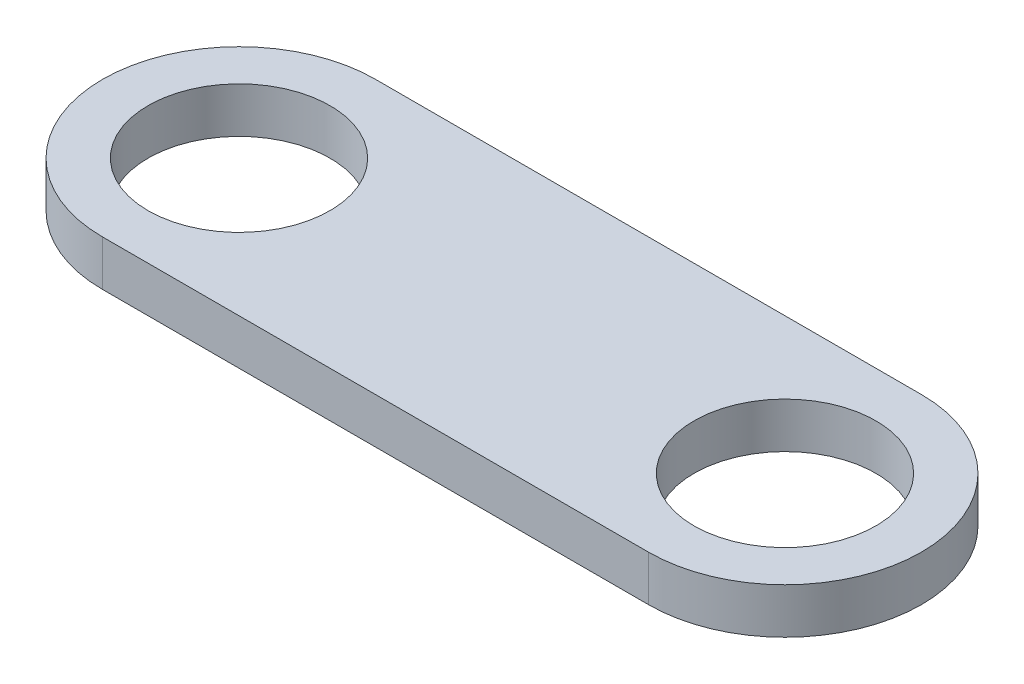
SolidWorks part; units mm, degrees
ref_plane "Front Plane" through (0, 0, 0) normal (0, 0, 1) x (1, 0, 0)
ref_plane "Top Plane" through (0, 0, 0) normal (0, 1, 0) x (1, 0, 0)
ref_plane "Right Plane" through (0, 0, 0) normal (1, 0, 0) x (0, 0, -1)
sketch "Sketch2" plane through (0, 0, 0) normal (0, 1, 0) x (1, 0, 0)
  line L0 (0, 0) -> (38.1, 0) construction
  line L1 (0, 9.525) -> (38.1, 9.525)
  line L2 (0, -9.525) -> (38.1, -9.525)
  arc A0 (0, 9.525) -> (0, -9.525) centre (0, 0) ccw
  arc A1 (38.1, -9.525) -> (38.1, 9.525) centre (38.1, 0) ccw
  circle A2 centre (0, 0) radius 6.35
  circle A3 centre (38.1, 0) radius 6.35
  point P3 (19.05, 0)
  dimension "D3" = 12.7
  dimension "D4" = 12.7
  dimension "D1" = 38.1
  dimension "D2" = 19.05
extrude "Boss-Extrude1" add sketch "Sketch2" along normal blind 3.175
